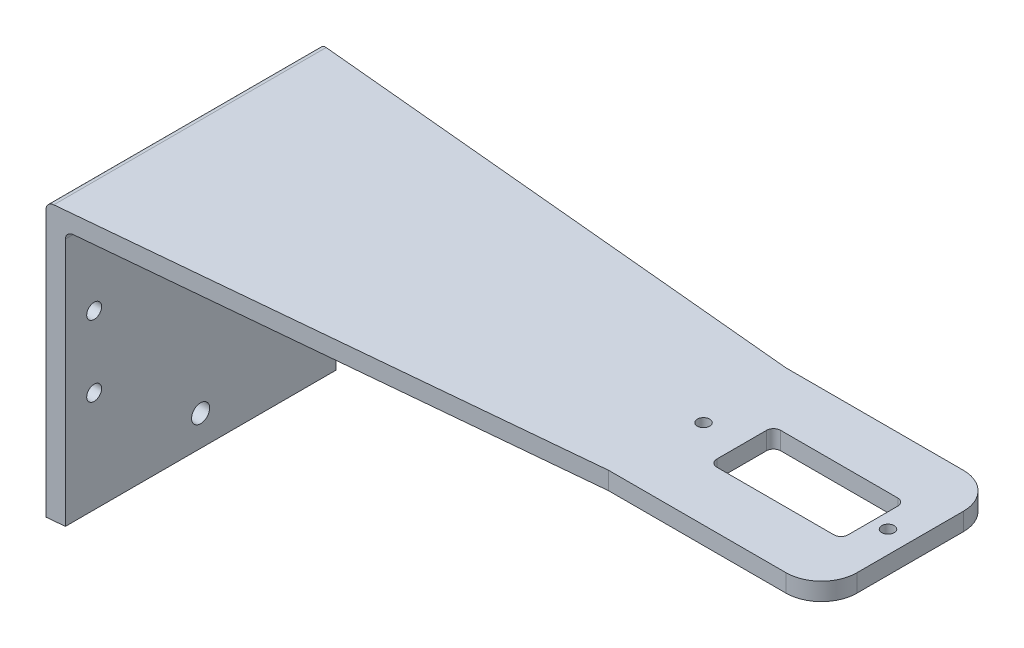
SolidWorks part; units mm, degrees
material "6061 Alloy"
ref_plane "Front" through (0, 0, 0) normal (0, 0, 1) x (1, 0, 0)
ref_plane "Top" through (0, 0, 0) normal (0, 1, 0) x (1, 0, 0)
ref_plane "Right" through (0, 0, 0) normal (1, 0, 0) x (0, 0, -1)
sketch "Sketch1" plane through (0, 0, 0) normal (0, 0, 1) x (1, 0, 0)
  line L0 (-29.1179, 28.3713) -> (-29.1179, -48.7787)
  line L1 (-29.1179, -48.7787) -> (-24.1179, -48.7787)
  line L2 (-24.1179, -48.7787) -> (-24.1179, 23.3713)
  line L3 (-24.1179, 23.3713) -> (175.8821, 23.3713)
  line L4 (175.8821, 23.3713) -> (175.8821, 28.3713)
  line L5 (175.8821, 28.3713) -> (-29.1179, 28.3713)
  dimension "D1" = 77.15
  dimension "D2" = 205
  dimension "D3" = 5
  dimension "D4" = 5
extrude "Boss-Extrude1" add sketch "Sketch1" along normal blind 77.15
sketch "Sketch2" plane through (0, 28.3713, 0) normal (0, 1, 0) x (1, 0, 0)
  line L0 (-29.1179, -38.575) -> (175.8821, -38.575) construction
  line L1 (-29.1179, -77.15) -> (-29.1179, 0) construction
  line L2 (175.8821, -77.15) -> (175.8821, 0) construction
  line L4 (175.8821, -13.575) -> (115.8821, -13.575)
  line L5 (115.8821, -13.575) -> (-29.1179, 0)
  line L6 (175.8821, -63.575) -> (115.8821, -63.575)
  line L7 (115.8821, -63.575) -> (-29.1179, -77.15)
  line L9 (128.3821, -29.575) -> (165.3821, -29.575)
  line L10 (128.3821, -29.575) -> (128.3821, -47.575)
  line L11 (128.3821, -47.575) -> (165.3821, -47.575)
  line L12 (165.3821, -29.575) -> (165.3821, -47.575)
  line L13 (-29.1179, 0) -> (175.8821, 0)
  line L14 (175.8821, 0) -> (175.8821, -13.575)
  line L15 (-29.1179, -77.15) -> (175.8821, -77.15)
  line L16 (175.8821, -77.15) -> (175.8821, -63.575)
  circle A0 centre (169.6321, -38.575) radius 1.75
  circle A1 centre (117.6321, -38.575) radius 1.75
  dimension "D6" = 3.5
  dimension "D7" = 10.5
  dimension "D5" = 6.25
  dimension "D1" = 50
  dimension "D2" = 60
  dimension "D3" = 37
  dimension "D4" = 18
  dimension "D8" = 52
extrude "Cut-Extrude1" cut sketch "Sketch2" against normal up to next
sketch "Sketch4" plane through (0, 23.3713, 0) normal (0, -1, 0) x (1, 0, 0)
  line L0 (115.8821, 63.575) -> (115.8821, 13.575)
  line L1 (115.8821, 63.575) -> (175.8821, 63.575)
  line L2 (175.8821, 63.575) -> (175.8821, 13.575)
  line L3 (175.8821, 13.575) -> (115.8821, 13.575)
split line "Split Line6"
fillet "Fillet1" radius 2 6 edges at (-24.1179, 23.3713, 38.575) (-29.1179, 28.3713, 38.575) (165.3821, 25.8713, 47.575) (128.3821, 25.8713, 47.575) (165.3821, 25.8713, 29.575) (128.3821, 25.8713, 29.575)
fillet "Fillet2" radius 10 2 edges at (175.8821, 25.8713, 13.575) (175.8821, 25.8713, 63.575)
sketch "Sketch6" plane through (-29.1179, 0, 0) normal (-1, 0, 0) x (0, 0, 1)
  line L8 (77.15, 28.3713) -> (0, 28.3713)
  line L9 (77.15, -48.7787) -> (0, -48.7787)
  line L10 (77.15, 28.3713) -> (77.15, -48.7787)
  line L11 (0, -48.7787) -> (0, 28.3713)
  line L12 (38.575, 28.3713) -> (38.575, -48.7787) construction
  circle A0 centre (18.575, -10.2037) radius 2.55 construction
  circle A1 centre (28.575, 9.7963) radius 2.55 construction
  circle A2 centre (48.575, 9.7963) radius 2.55 construction
  circle A3 centre (58.575, -10.2037) radius 2.55 construction
  circle A4 centre (48.575, -30.2037) radius 2.55 construction
  circle A5 centre (28.575, -30.2037) radius 2.55 construction
  circle A6 centre (18.575, -30.2037) radius 2.1 construction
  circle A7 centre (18.575, 9.7963) radius 2.1 construction
  circle A8 centre (58.575, 9.7963) radius 2.1 construction
  circle A9 centre (58.575, -30.2037) radius 2.1 construction
  circle A10 centre (8.575, 19.7963) radius 2.55 construction
  circle A11 centre (68.575, 19.7963) radius 2.55 construction
  circle A12 centre (68.575, -40.2037) radius 2.55 construction
  circle A13 centre (8.575, -40.2037) radius 2.55 construction
  circle A14 centre (8.575, -20.2037) radius 2.1
  circle A15 centre (8.575, -0.2037) radius 2.1
  circle A16 centre (38.575, 19.7963) radius 2.55 construction
  circle A17 centre (38.575, -40.2037) radius 2.55
  circle A18 centre (68.575, -20.2037) radius 2.1
  circle A19 centre (68.575, -0.2037) radius 2.1
  point P42 (38.575, -10.2037)
  point P43 (77.15, -48.7787)
  point P48 (77.15, -48.7787)
  point P49 (77.15, 28.3713)
  point P51 (0, 28.3713)
  point P53 (0, -48.7787)
  point P55 (0, -48.7787)
extrude "Cut-Extrude2" cut sketch "Sketch6" against normal up to next (5 mm away) flip side to cut
